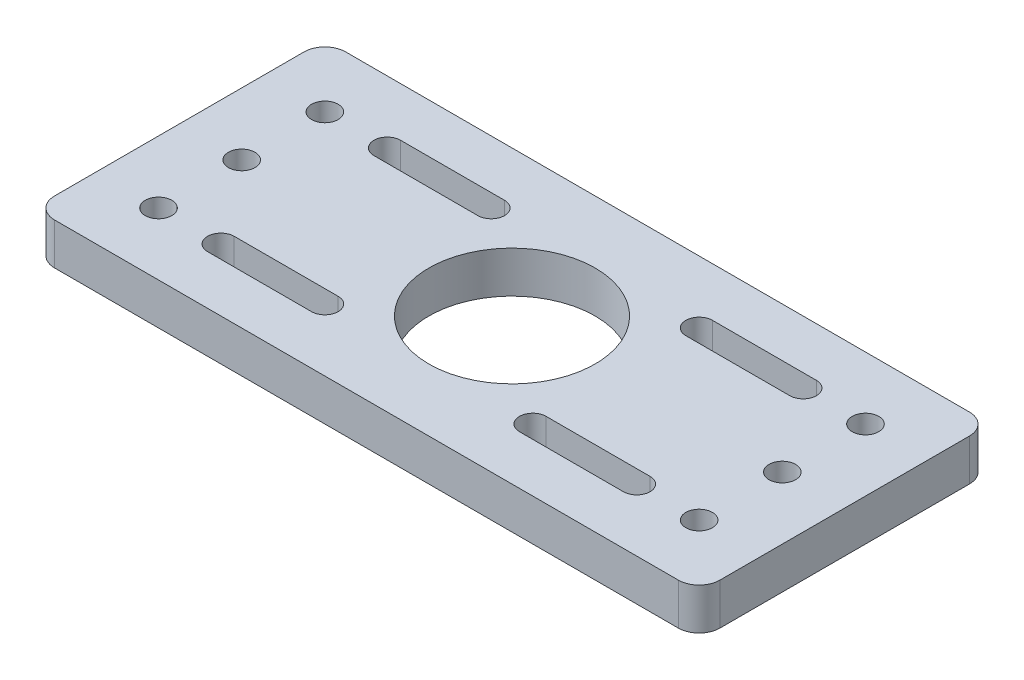
SolidWorks part; units mm, degrees
ref_plane "Front Plane" through (0, 0, 0) normal (0, 0, 1) x (1, 0, 0)
ref_plane "Top Plane" through (0, 0, 0) normal (0, 1, 0) x (1, 0, 0)
ref_plane "Right Plane" through (0, 0, 0) normal (1, 0, 0) x (0, 0, -1)
sketch "Sketch1" plane through (0, 0, 0) normal (0, 1, 0) x (1, 0, 0)
  line L0 (19.05, 88.9) -> (19.05, 0) construction
  line L1 (0, 0) -> (203.2, 0)
  line L2 (0, 0) -> (0, 88.9)
  line L3 (0, 88.9) -> (203.2, 88.9)
  line L4 (203.2, 0) -> (203.2, 88.9)
  line L5 (101.6, 88.9) -> (101.6, 0) construction
  line L6 (38.1, 69.85) -> (69.85, 69.85) construction
  line L9 (38.1, 73.914) -> (69.85, 73.914)
  line L10 (38.1, 65.786) -> (69.85, 65.786)
  line L11 (38.1, 69.85) -> (19.05, 69.85) construction
  line L12 (0, 44.45) -> (101.6, 44.45) construction
  line L13 (38.1, 19.05) -> (69.85, 19.05) construction
  line L14 (38.1, 14.986) -> (69.85, 14.986)
  line L15 (38.1, 23.114) -> (69.85, 23.114)
  line L16 (165.1, 19.05) -> (133.35, 19.05) construction
  line L17 (165.1, 14.986) -> (133.35, 14.986)
  line L18 (165.1, 23.114) -> (133.35, 23.114)
  line L19 (165.1, 69.85) -> (133.35, 69.85) construction
  line L20 (165.1, 73.914) -> (133.35, 73.914)
  line L21 (165.1, 65.786) -> (133.35, 65.786)
  circle A0 centre (101.6, 44.45) radius 25.4
  circle A1 centre (19.05, 19.05) radius 4.064
  circle A2 centre (19.05, 44.45) radius 4.064
  circle A3 centre (19.05, 69.85) radius 4.064
  circle A4 centre (184.15, 69.85) radius 4.064
  circle A5 centre (184.15, 44.45) radius 4.064
  circle A6 centre (184.15, 19.05) radius 4.064
  arc A9 (38.1, 73.914) -> (38.1, 65.786) centre (38.1, 69.85) ccw
  arc A10 (69.85, 65.786) -> (69.85, 73.914) centre (69.85, 69.85) ccw
  arc A11 (38.1, 14.986) -> (38.1, 23.114) centre (38.1, 19.05) cw
  arc A12 (69.85, 23.114) -> (69.85, 14.986) centre (69.85, 19.05) cw
  arc A13 (165.1, 14.986) -> (165.1, 23.114) centre (165.1, 19.05) ccw
  arc A14 (133.35, 23.114) -> (133.35, 14.986) centre (133.35, 19.05) ccw
  arc A15 (165.1, 73.914) -> (165.1, 65.786) centre (165.1, 69.85) cw
  arc A16 (133.35, 65.786) -> (133.35, 73.914) centre (133.35, 69.85) cw
  point P25 (53.975, 69.85)
  point P34 (53.975, 19.05)
  point P41 (149.225, 19.05)
  point P48 (149.225, 69.85)
  dimension "D4" = 50.8
  dimension "D5" = 8.128
  dimension "D1" = 19.05
  dimension "D2" = 88.9
  dimension "D3" = 203.2
  dimension "D7" = 19.05
  dimension "D8" = 25.4
  dimension "D9" = 8.128
  dimension "D10" = 38.1
  dimension "D11" = 31.75
  dimension "D6" = 3
extrude "Boss-Extrude1" add sketch "Sketch1" along normal blind 12.7
fillet "Fillet1" radius 6.35 4 edges at (0, 6.35, -88.9) (203.2, 6.35, -88.9) (203.2, 6.35, 0) (0, 6.35, 0)
